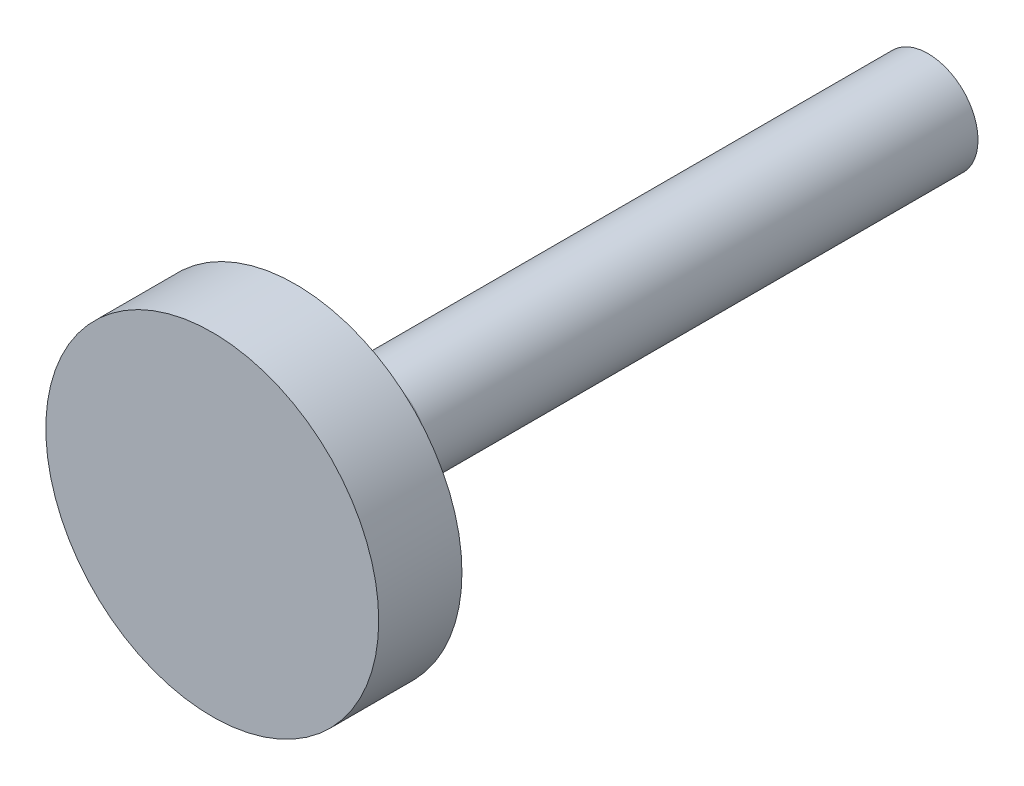
SolidWorks part; units mm, degrees
ref_plane "Front Plane" through (0, 0, 0) normal (0, 0, 1) x (1, 0, 0)
ref_plane "Top Plane" through (0, 0, 0) normal (0, 1, 0) x (1, 0, 0)
ref_plane "Right Plane" through (0, 0, 0) normal (1, 0, 0) x (0, 0, -1)
sketch "Sketch1" plane through (0, 0, 0) normal (0, 0, 1) x (1, 0, 0)
  circle A0 centre (0, 0) radius 3
  dimension "D1" = 6
extrude "Boss-Extrude1" add sketch "Sketch1" along normal blind 38
sketch "Sketch2" plane through (0, 0, 38) normal (0, 0, 1) x (1, 0, 0)
  circle A0 centre (0, 0) radius 10
  dimension "D1" = 20
extrude "Boss-Extrude2" add sketch "Sketch2" along normal blind 5
fillet "Fillet1" radius 5 1 edges at (3, 0, 38)
